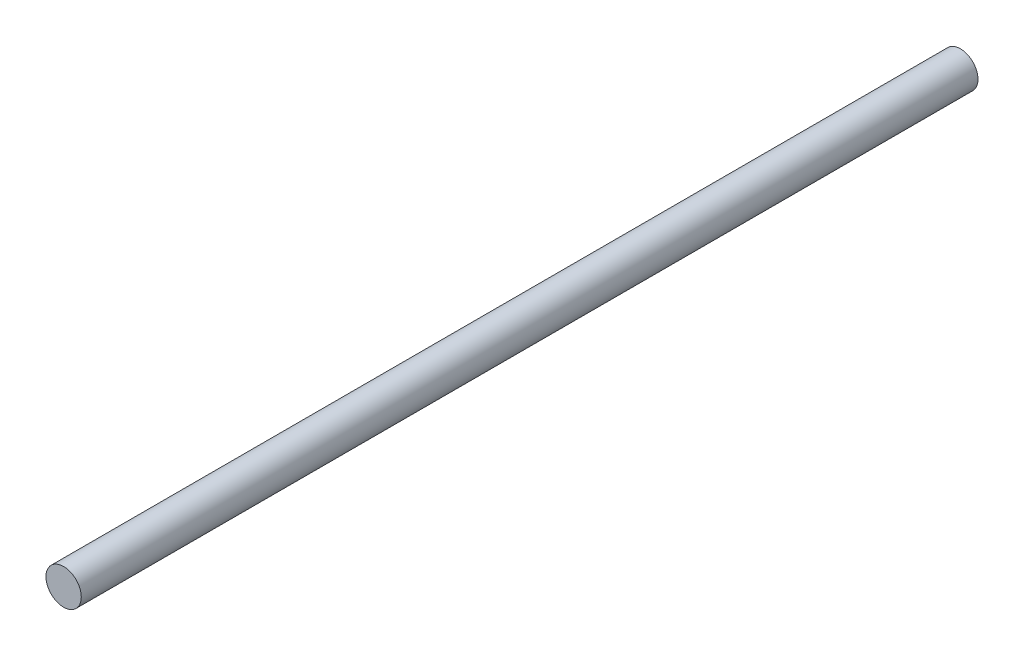
SolidWorks part; units mm, degrees
ref_plane "Plan de face" through (0, 0, 0) normal (0, 0, 1) x (1, 0, 0)
ref_plane "Plan de dessus" through (0, 0, 0) normal (0, 1, 0) x (1, 0, 0)
ref_plane "Plan de droite" through (0, 0, 0) normal (1, 0, 0) x (0, 0, -1)
sketch "Esquisse1" plane through (0, 0, 0) normal (0, 0, 1) x (1, 0, 0)
  circle A0 centre (0, 0) radius 2.5
  dimension "D1" = 5
extrude "Boss.-Extru.1" add sketch "Esquisse1" along normal blind 127
